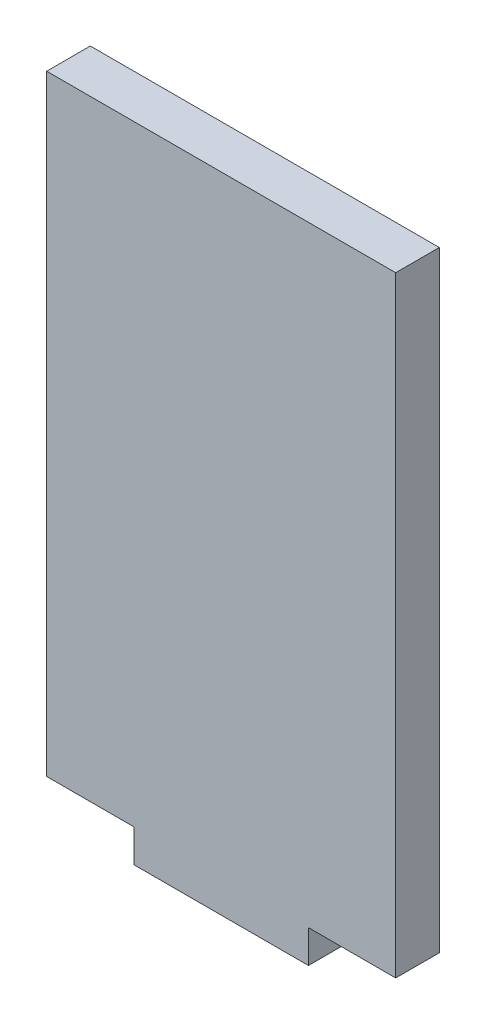
SolidWorks part; units mm, degrees
ref_plane "Front Plane" through (0, 0, 0) normal (0, 0, 1) x (1, 0, 0)
ref_plane "Top Plane" through (0, 0, 0) normal (0, 1, 0) x (1, 0, 0)
ref_plane "Right Plane" through (0, 0, 0) normal (1, 0, 0) x (0, 0, -1)
sketch "Sketch1" plane through (0, 0, 0) normal (0, 0, 1) x (1, 0, 0)
  line L0 (6.35, 0) -> (6.35, -2.3879)
  line L1 (0, 0) -> (6.35, 0)
  line L2 (0, 0) -> (0, 44.45)
  line L3 (0, 44.45) -> (25.4, 44.45)
  line L4 (25.4, 0) -> (25.4, 44.45)
  line L5 (6.35, -2.3879) -> (19.05, -2.3879)
  line L6 (19.05, -2.3879) -> (19.05, 0)
  line L7 (12.7, -2.3879) -> (12.7, 0) construction
  line L8 (19.05, 0) -> (25.4, 0)
  dimension "D1" = 25.4
  dimension "D2" = 44.45
  dimension "D3" = 12.7
extrude "Boss-Extrude1" add sketch "Sketch1" along normal blind 3.175
